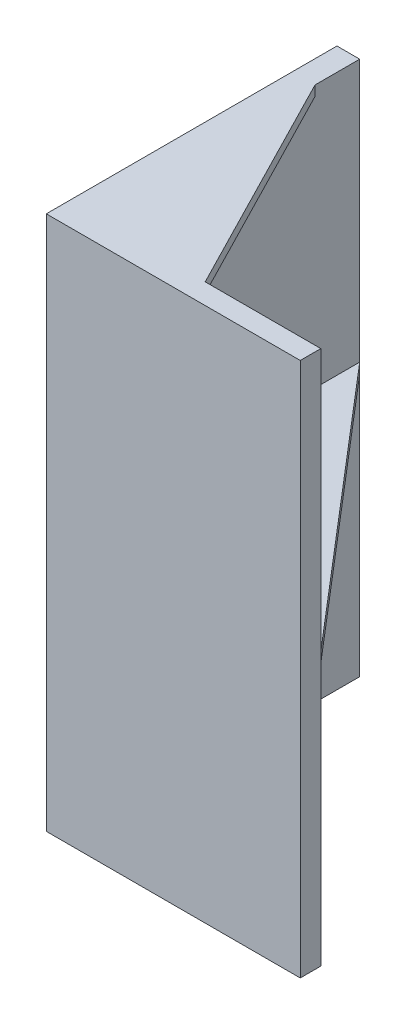
SolidWorks part; units mm, degrees
ref_plane "Front Plane" through (0, 0, 0) normal (0, 0, 1) x (1, 0, 0)
ref_plane "Top Plane" through (0, 0, 0) normal (0, 1, 0) x (1, 0, 0)
ref_plane "Right Plane" through (0, 0, 0) normal (1, 0, 0) x (0, 0, -1)
sketch "Sketch1" plane through (0, 0, 0) normal (0, 1, 0) x (1, 0, 0)
  line L1 (-11.5628, 77.9555) -> (0, 77.9555)
  line L2 (-11.5628, 77.9555) -> (-11.5628, -59.3059)
  line L4 (0, 77.9555) -> (0, -59.3059)
  line L5 (0, -59.3059) -> (117.4927, -59.3059)
  line L6 (-11.5628, -59.3059) -> (-11.5628, -69.7497)
  line L7 (-11.5628, -69.7497) -> (117.4927, -69.7497)
  line L8 (117.4927, -59.3059) -> (117.4927, -69.7497)
extrude "Boss-Extrude2" add sketch "Sketch1" against normal mid plane 271.78
sketch "Sketch4" plane through (0, 135.89, 0) normal (0, 1, 0) x (1, 0, 0)
  line L0 (0, 55.2334) -> (58.7464, -59.3059)
  line L1 (0, -59.3059) -> (0, 77.9555) construction
  line L2 (117.4927, -59.3059) -> (0, -59.3059) construction
  point P6 (0, 55.2334)
  point P7 (58.7464, -59.3059)
rib "Rib18" sketch "Sketch4" sketch "Sketch4" thickness 5.08 extrusion direction parallel to sketch draft on no parameters "D1"=5.08
sketch "Sketch5" plane through (0, -135.89, 0) normal (0, -1, 0) x (1, 0, 0)
  line L0 (0, 0) -> (72.2654, 59.3059)
  line L1 (117.4927, 59.3059) -> (0, 59.3059) construction
  point P5 (0, 0)
  point P6 (0, 0)
  point P7 (0, 0)
sketch "Sketch6" plane through (0, 0, 0) normal (0, 1, 0) x (1, 0, 0)
  line L0 (0, 77.9555) -> (117.4927, -59.3059)
rib "Rib27" sketch "Sketch6" sketch "Sketch6" thickness 5.08 extrusion direction parallel to sketch draft on no parameters "D1"=5.08
